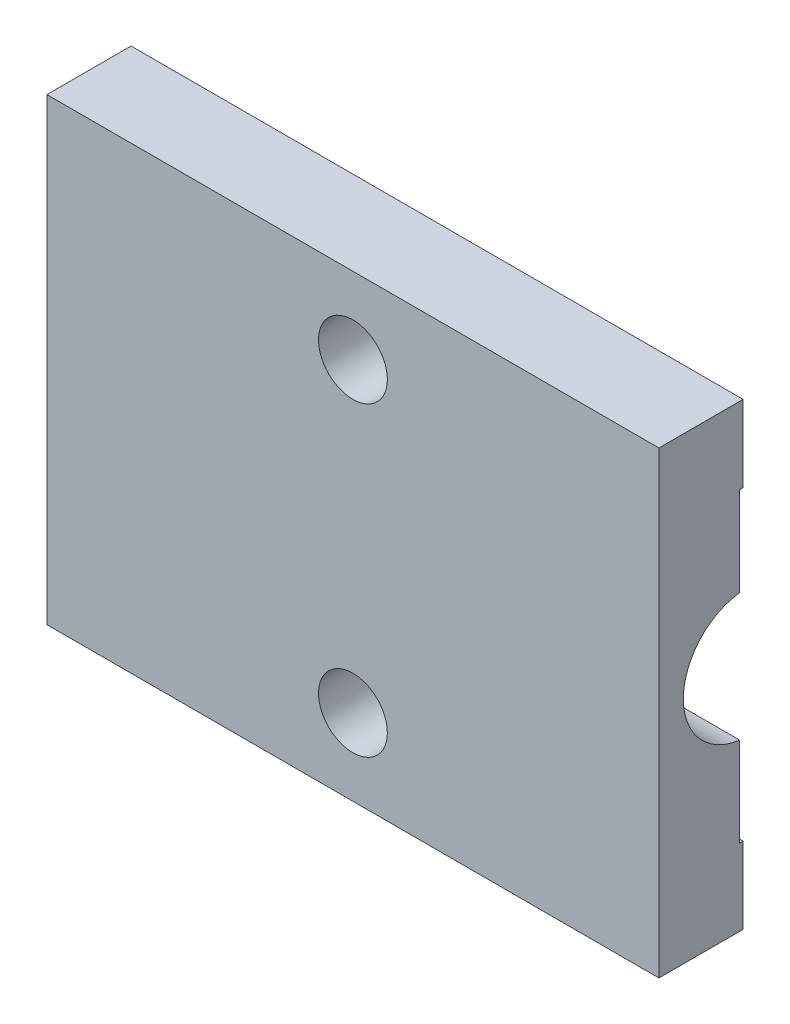
SolidWorks part; units mm, degrees
ref_plane "Front Plane" through (0, 0, 0) normal (0, 0, 1) x (1, 0, 0)
ref_plane "Top Plane" through (0, 0, 0) normal (0, 1, 0) x (1, 0, 0)
ref_plane "Right Plane" through (0, 0, 0) normal (1, 0, 0) x (0, 0, -1)
sketch "Sketch1" plane through (0, 0, 0) normal (0, 0, 1) x (1, 0, 0)
  line L1 (-20, -15) -> (20, -15)
  line L2 (-20, -15) -> (-20, 15)
  line L3 (-20, 15) -> (20, 15)
  line L4 (20, -15) -> (20, 15)
  line L5 (-20, -15) -> (20, 15) construction
  line L6 (-20, 15) -> (20, -15) construction
  point P1 (0, 0)
  dimension "D1" = 40
  dimension "D2" = 30
extrude "Boss-Extrude1" add sketch "Sketch1" along normal blind 5.5
sketch "Sketch2" plane through (20, 0, 0) normal (1, 0, 0) x (0, 0, -1)
  circle A0 centre (0.3, 0) radius 4.205
  dimension "D1" = 8.41
  dimension "D2" = 0.3
extrude "Cut-Extrude1" cut sketch "Sketch2" against normal through all
hole_wizard "M4 Clearance Hole1" positions "Sketch6" profile "Sketch4" hole size "M4" standard "ANSI Metric" end condition through all
sketch "Sketch6" plane through (0, 0, 5.5) normal (0, 0, 1) x (1, 0, 0)
  line L0 (20, 15) -> (-20, 15) construction
  line L1 (-20, -15) -> (20, -15) construction
  point P0 (0, 10)
  point P2 (0, -10)
  point P7 (0, 15)
  point P10 (0, -15)
  dimension "D1" = 5
  dimension "D2" = 5
sketch "Sketch4" plane through (0, 10, 5.5) normal (1, 0, 0) x (0, -1, 0)
  line L0 (0, 0) -> (0, 5.5)
  line L1 (0, 5.5) -> (2.25, 5.5)
  line L2 (2.25, 5.5) -> (2.25, 0)
  line L5 (2.25, 0) -> (0, 0)
  line L11 (0, -6.35) -> (0, 107.95) construction
  dimension "Thru Hole Dia." = 4.5
  dimension "Thru Hole Depth" = 5.5
sketch "Sketch7" plane through (20, 0, 0) normal (1, 0, 0) x (0, 0, -1)
  line L1 (-0.225, 10) -> (0.825, 10)
  line L2 (-0.225, 10) -> (-0.225, -10)
  line L3 (-0.225, -10) -> (0.825, -10)
  line L4 (0.825, 10) -> (0.825, -10)
  line L5 (-0.225, 10) -> (0.825, -10) construction
  line L6 (-0.225, -10) -> (0.825, 10) construction
  arc A0 (0, 4.1943) -> (0, -4.1943) centre (0.3, 0) ccw construction
  arc A1 (0, 4.1943) -> (0, -4.1943) centre (0.3, 0) ccw construction
  dimension "D1" = 1.05
  dimension "D2" = 20
extrude "Cut-Extrude2" cut sketch "Sketch7" against normal blind 10
